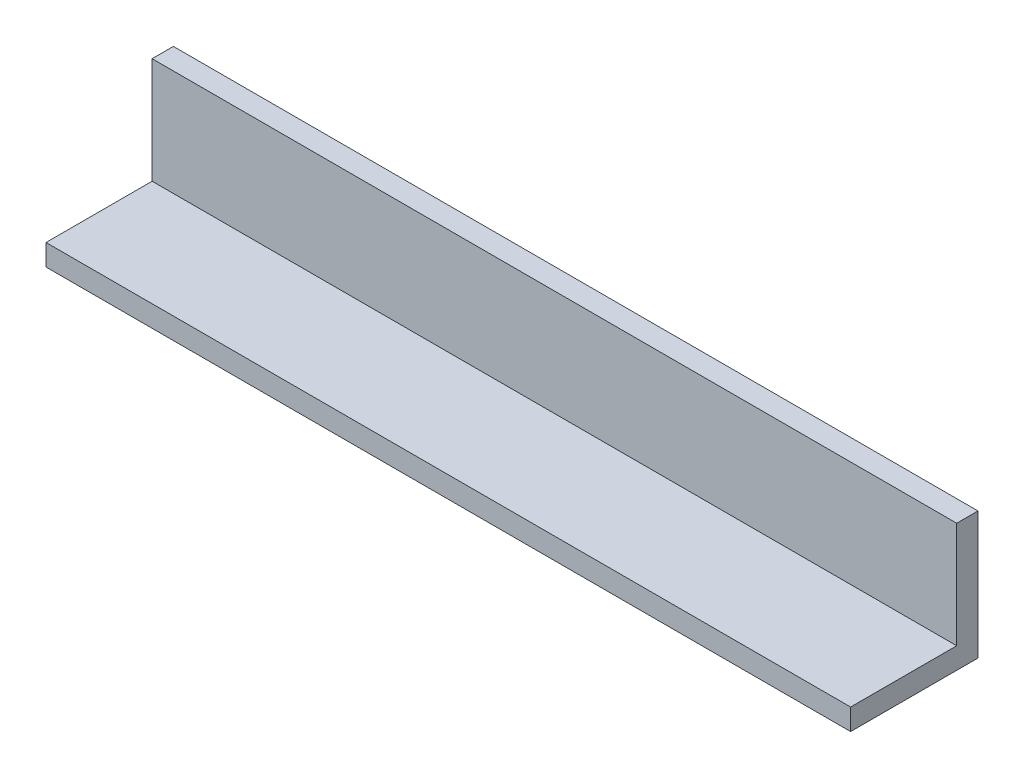
SolidWorks part; units mm, degrees
ref_plane "Alzado" through (0, 0, 0) normal (0, 0, 1) x (1, 0, 0)
ref_plane "Planta" through (0, 0, 0) normal (0, 1, 0) x (1, 0, 0)
ref_plane "Vista lateral" through (0, 0, 0) normal (1, 0, 0) x (0, 0, -1)
sketch "Croquis1" plane through (0, 0, 0) normal (0, 1, 0) x (1, 0, 0)
  line L1 (-120, 19) -> (120, 19)
  line L2 (-120, 19) -> (-120, -19)
  line L3 (-120, -19) -> (120, -19)
  line L4 (120, 19) -> (120, -19)
  line L5 (-120, 19) -> (120, -19) construction
  line L6 (-120, -19) -> (120, 19) construction
  point P0 (0, 0)
extrude "Saliente-Extruir1" add sketch "Croquis1" along normal blind 6.35
sketch "Croquis2" plane through (0, 6.35, 0) normal (0, 1, 0) x (1, 0, 0)
  line L1 (-120, 19) -> (120, 19)
  line L2 (-120, 19) -> (-120, 12.65)
  line L3 (-120, 12.65) -> (120, 12.65)
  line L4 (120, 19) -> (120, 12.65)
extrude "Saliente-Extruir2" add sketch "Croquis2" along normal blind 31.65
